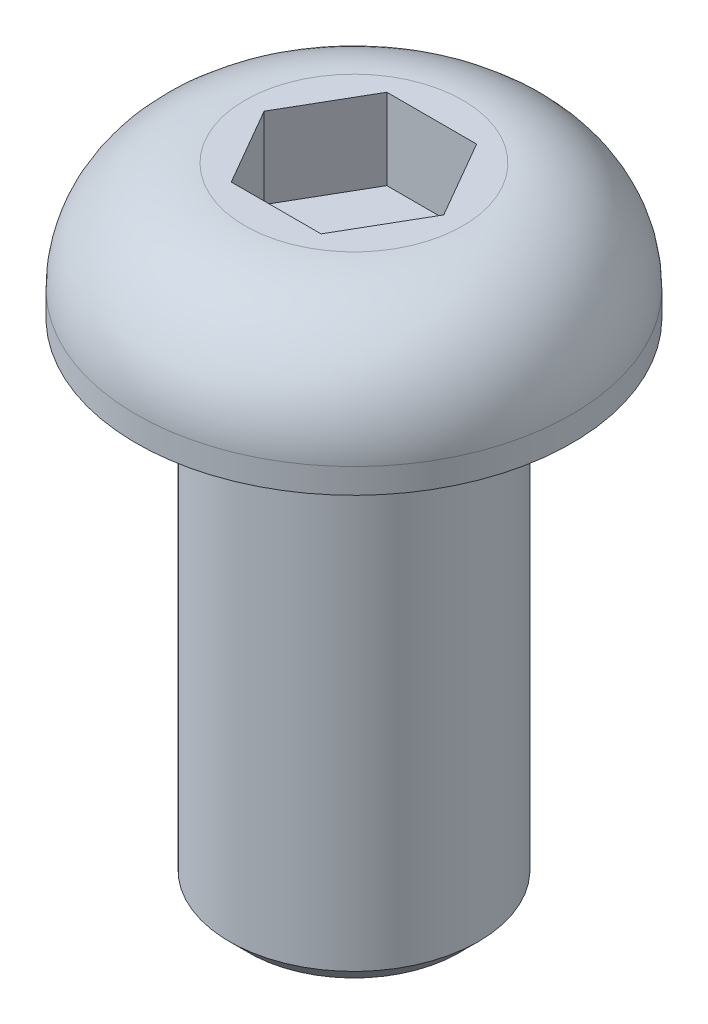
SolidWorks part; units mm, degrees
material "Plain Carbon Steel"
ref_plane "Front Plane" through (0, 0, 0) normal (0, 0, 1) x (1, 0, 0)
ref_plane "Top Plane" through (0, 0, 0) normal (0, 1, 0) x (1, 0, 0)
ref_plane "Right Plane" through (0, 0, 0) normal (1, 0, 0) x (0, 0, -1)
sketch "Sketch1" plane through (0, 0, 0) normal (0, 0, 1) x (1, 0, 0)
  line L0 (0, 0) -> (3.5, 0)
  line L1 (7, -3.5) -> (7, -4.3)
  line L2 (7, -4.3) -> (4, -4.3)
  line L3 (4, -4.3) -> (4, -20.3)
  line L4 (4, -20.3) -> (0, -20.3)
  line L5 (0, -20.3) -> (0, 0)
  line L6 (0, 5) -> (0, -25.3) construction
  arc A0 (3.5, 0) -> (7, -3.5) centre (3.5, -3.5) cw
  dimension "D1" = 5
  dimension "D2" = 5
  dimension "D3" = 8
  dimension "D4" = 14
  dimension "D5" = 4.3
  dimension "D6" = 0.8
  dimension "L" = 16
revolve "Revolve1" add sketch "Sketch1" angle 360 about L6
sketch "Sketch2" plane through (0, 0, 0) normal (0, 1, 0) x (1, 0, 0)
  line L1 (2.8868, 0) -> (1.4434, 2.5)
  line L2 (1.4434, 2.5) -> (-1.4434, 2.5)
  line L3 (-1.4434, 2.5) -> (-2.8868, 0)
  line L4 (-2.8868, 0) -> (-1.4434, -2.5)
  line L5 (-1.4434, -2.5) -> (1.4434, -2.5)
  line L6 (1.4434, -2.5) -> (2.8868, 0)
  circle A0 centre (0, 0) radius 2.5 construction
  dimension "D1" = 5
extrude "Cut-Extrude1" cut sketch "Sketch2" against normal blind 2.6
fillet "Fillet1" radius 0.4 1 edges at (-4, -4.3, 0)
chamfer "Chamfer1" distance 0.625 angle 45 1 edges at (-4, -20.3, 0)
cosmetic thread "Cosmetic Thread1" parameters "B"=12.25, "D2"=6.619
